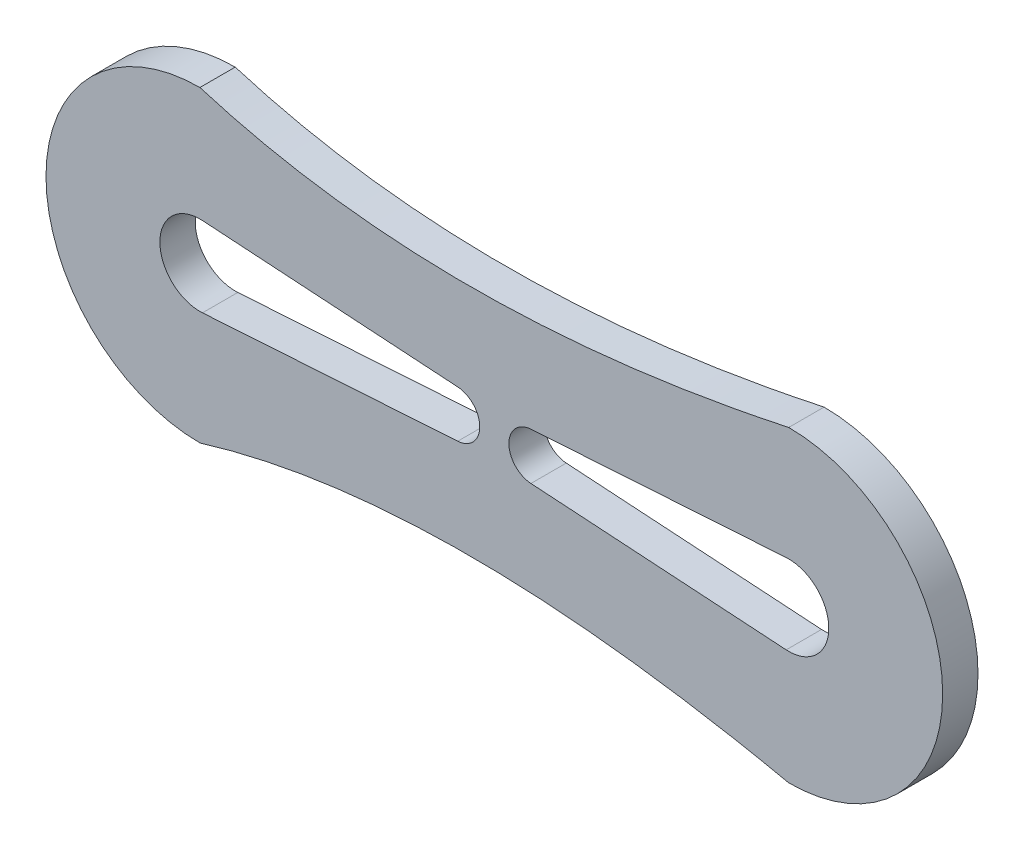
SolidWorks part; units mm, degrees
ref_plane "Front Plane" through (0, 0, 0) normal (0, 0, 1) x (1, 0, 0)
ref_plane "Top Plane" through (0, 0, 0) normal (0, 1, 0) x (1, 0, 0)
ref_plane "Right Plane" through (0, 0, 0) normal (1, 0, 0) x (0, 0, -1)
sketch "Sketch1" plane through (0, 0, 0) normal (0, 0, 1) x (1, 0, 0)
  line L0 (0, 48.486) -> (0, -17.0326) construction
  line L1 (-25, 0) -> (25, 0) construction
  line L2 (-24.7813, 3.393) -> (-3.1073, 1.9959)
  line L3 (-24.7813, -3.393) -> (-3.1073, -1.9959)
  line L4 (24.7813, -3.393) -> (3.1073, -1.9959)
  line L5 (24.7813, 3.393) -> (3.1073, 1.9959)
  line L6 (25, 13.069) -> (25, -13.069) construction
  arc A0 (-24.7813, 3.393) -> (-24.7813, -3.393) centre (-25, 0) ccw
  arc A1 (-3.1073, -1.9959) -> (-3.1073, 1.9959) centre (-3.236, 0) ccw
  arc A2 (3.1073, -1.9959) -> (3.1073, 1.9959) centre (3.236, 0) cw
  arc A3 (24.7813, 3.393) -> (24.7813, -3.393) centre (25, 0) cw
  arc A4 (-12.1884, 2.5812) -> (-12.1884, -2.5812) centre (-25, 0) ccw
  circle A5 centre (25, 0) radius 13.069
  circle A8 centre (25, 0) radius 1
  circle A9 centre (-25, 0) radius 1
  spline S0 degree 2 poles (-25, 13.069) (-4.3275, 6.7524) (25, 13.069) knots 0 0 0 1 1 1
  spline S1 degree 2 poles (-25, -13.069) (-4.3275, -6.7524) (25, -13.069) knots 0 0 0 1 1 1
  dimension "D2" = 6.8
  dimension "D3" = 4
  dimension "D5" = 26.138
  dimension "D8" = 2
  dimension "D1" = 25
  dimension "D4" = 3.236
  dimension "D6" = 48.486
extrude "Boss-Extrude2" add sketch "Sketch1" along normal blind 3 contours A4 S1 L3 A0 L2 S0 | A4 S1 A5 L4 A2 L5 S0 L2 A1 L3 | A5 S1 S0 L5 A3 L4
